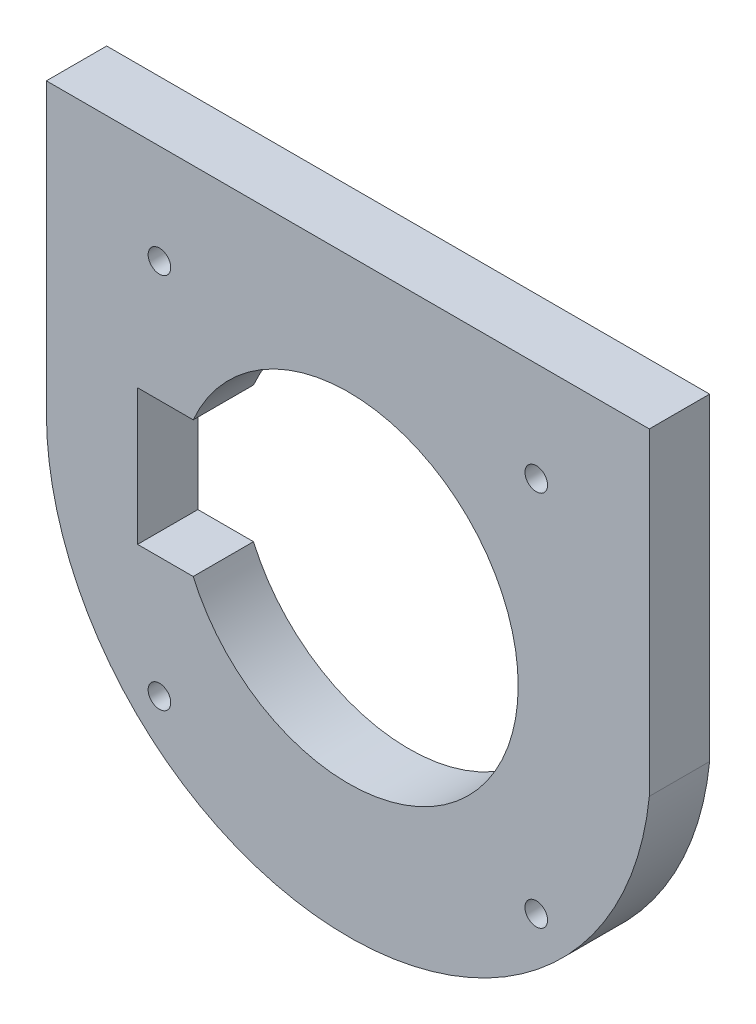
SolidWorks part; units mm, degrees
ref_plane "前视基准面" through (0, 0, 0) normal (0, 0, 1) x (1, 0, 0)
ref_plane "上视基准面" through (0, 0, 0) normal (0, 1, 0) x (1, 0, 0)
ref_plane "右视基准面" through (0, 0, 0) normal (1, 0, 0) x (0, 0, -1)
sketch "草图1" plane through (0, 0, 0) normal (0, 0, 1) x (1, 0, 0)
  line L1 (0, 0) -> (100, 0)
  line L2 (0, 0) -> (0, 100)
  line L3 (0, 100) -> (100, 100)
  line L4 (100, 0) -> (100, 100)
  dimension "D1" = 100
  dimension "D2" = 100
extrude "凸台-拉伸1" add sketch "草图1" along normal blind 8
ref_plane "基准面1" through (50, 0, 0) normal (1, 0, 0) x (0, 0, -1)
sketch "草图2" plane through (0, 0, 8) normal (0, 0, 1) x (1, 0, 0)
  line L0 (50.1, 59.3) -> (50.1, 112.5879) construction
  line L1 (50.1, 59.3) -> (118.0397, 59.3) construction
  line L2 (90, 97.5176) -> (90, 55.3) construction
  line L3 (10, 59.3) -> (10, 97.5176) construction
  line L4 (90, 97.5176) -> (90, 55.3)
  line L5 (10, 59.3) -> (10, 97.5176)
  line L6 (10, 97.5176) -> (90, 97.5176)
  arc A0 (10, 59.3) -> (90, 55.3) centre (50.1, 59.3) ccw construction
  arc A1 (10, 59.3) -> (90, 55.3) centre (50.1, 59.3) ccw
extrude "切除-拉伸1" cut sketch "草图2" against normal through all flip side to cut
sketch "草图3" plane through (0, 0, 8) normal (0, 0, 1) x (1, 0, 0)
  line L0 (50, 97.5176) -> (50, 8.4769) construction
  line L1 (90, 97.5176) -> (10, 97.5176) construction
  line L2 (50.1, 59.3) -> (102.4751, 59.3) construction
  line L4 (29.4784, 68.3) -> (22.1, 68.3)
  line L6 (29.4784, 50.3) -> (22.1, 50.3)
  line L7 (22.1, 68.3) -> (22.1, 50.3)
  circle A0 centre (75, 84.3) radius 1.5
  circle A1 centre (75, 34.3) radius 1.5
  circle A2 centre (25, 34.3) radius 1.5
  circle A3 centre (25, 84.3) radius 1.5
  arc A4 (29.4784, 50.3) -> (29.4784, 68.3) centre (50.1, 59.3) ccw
  dimension "D1" = 3
  dimension "D3" = 25
  dimension "D4" = 45
  dimension "D2" = 25
  dimension "D5" = 18
  dimension "D6" = 28
  dimension "D7" = 18
extrude "切除-拉伸2" cut sketch "草图3" against normal through all
